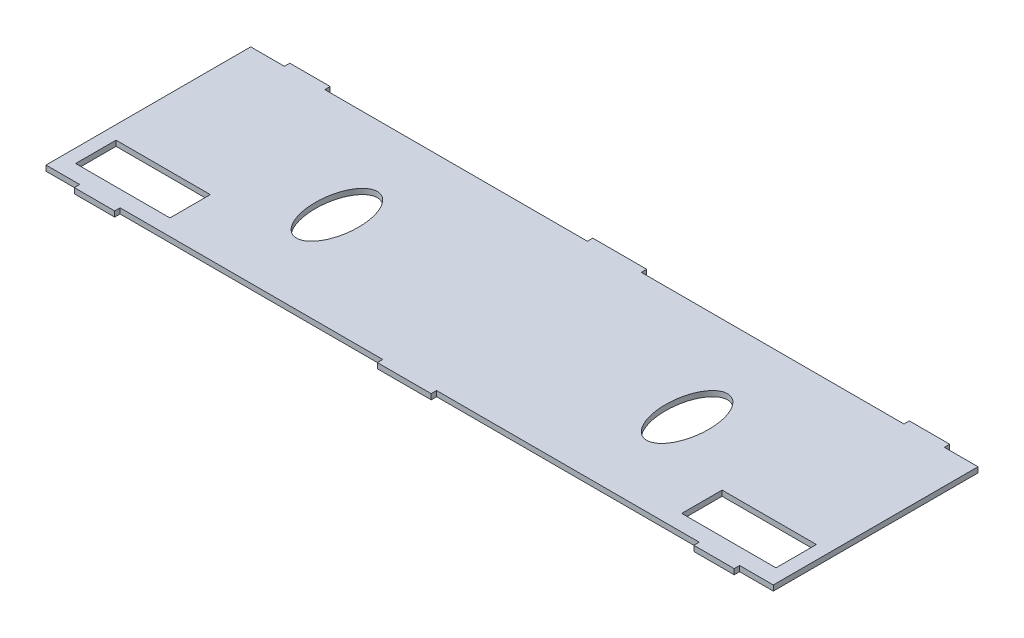
SolidWorks part; units mm, degrees
material "Hexcel AS4C (3000 丝)"
ref_plane "前视基准面" through (0, 0, 0) normal (0, 0, 1) x (1, 0, 0)
ref_plane "上视基准面" through (0, 0, 0) normal (0, 1, 0) x (1, 0, 0)
ref_plane "右视基准面" through (0, 0, 0) normal (1, 0, 0) x (0, 0, -1)
sketch "草图1" plane through (0, 0, 0) normal (0, 1, 0) x (1, 0, 0)
  line L0 (-107.5, 38) -> (-10, 38)
  line L1 (-135, -38) -> (-122.5, -38)
  line L2 (-135, -38) -> (-135, 38)
  line L3 (-135, 38) -> (-122.5, 38)
  line L4 (135, -38) -> (135, 38)
  line L5 (-135, -38) -> (135, 38) construction
  line L6 (-135, 38) -> (135, -38) construction
  line L7 (-122.5, 40) -> (-107.5, 40)
  line L8 (-122.5, 40) -> (-122.5, 38)
  line L9 (10, 38) -> (107.5, 38)
  line L10 (-107.5, 40) -> (-107.5, 38)
  line L11 (-122.5, 40) -> (-107.5, 38) construction
  line L12 (-122.5, 38) -> (-107.5, 40) construction
  line L13 (122.5, 38) -> (135, 38)
  line L14 (-10, 38) -> (-10, 40)
  line L15 (-10, 40) -> (10, 40)
  line L16 (10, 38) -> (10, 40)
  line L17 (-10, 38) -> (10, 40) construction
  line L18 (-10, 40) -> (10, 38) construction
  line L19 (107.5, 40) -> (122.5, 40)
  line L20 (107.5, 40) -> (107.5, 38)
  line L21 (-135, 0) -> (135, 0) construction
  line L22 (122.5, 40) -> (122.5, 38)
  line L23 (107.5, 40) -> (122.5, 38) construction
  line L24 (107.5, 38) -> (122.5, 40) construction
  line L25 (107.5, -40) -> (107.5, -38)
  line L26 (107.5, -40) -> (122.5, -40)
  line L27 (122.5, -40) -> (122.5, -38)
  line L28 (-10, -38) -> (-10, -40)
  line L29 (10, -38) -> (10, -40)
  line L30 (-10, -40) -> (10, -40)
  line L31 (-107.5, -40) -> (-107.5, -38)
  line L32 (-122.5, -40) -> (-122.5, -38)
  line L33 (-122.5, -40) -> (-107.5, -40)
  line L34 (-107.5, -38) -> (-10, -38)
  line L35 (10, -38) -> (107.5, -38)
  line L36 (122.5, -38) -> (135, -38)
  line L37 (0, -39) -> (0, 39) construction
  ellipse E0 centre (-65, 0) end of major axis (-65, 15) minor radius 8
  ellipse E1 centre (65, 0) end of major axis (65, 15) minor radius 8
  point P0 (0, 0)
  point P6 (-115, 39)
  point P11 (0, 39)
  point P16 (115, 39)
  point P24 (0, 0)
  point P36 (-115, -39)
  point P46 (0, 0)
  dimension "D1" = 270
  dimension "D2" = 76
  dimension "D3" = 15
  dimension "D4" = 2
  dimension "D5" = 20
  dimension "D6" = 2
  dimension "D7" = 20
  dimension "D8" = 65
  dimension "D9" = 2
  dimension "D10" = 15
  dimension "D11" = 20
  dimension "D12" = 15
  dimension "D13" = 8
extrude "凸台-拉伸1" add sketch "草图1" along normal blind 2
sketch "草图2" plane through (0, 0, 0) normal (0, -1, 0) x (1, 0, 0)
  line L0 (-135, -38) -> (-135, 38) construction
  line L1 (-95, 17) -> (-130, 17)
  line L2 (-95, 17) -> (-95, 32)
  line L3 (-95, 32) -> (-130, 32)
  line L4 (-130, 17) -> (-130, 32)
  line L5 (-95, 17) -> (-130, 32) construction
  line L6 (-95, 32) -> (-130, 17) construction
  line L7 (-107.5, 38) -> (-10, 38) construction
  point P0 (-112.5, 24.5)
  dimension "D1" = 5
  dimension "D2" = 6
  dimension "D3" = 15
  dimension "D4" = 35
extrude "切除-拉伸1" cut sketch "草图2" against normal through all
mirror "镜向1" about plane through (0, 0, 0) normal (1, 0, 0) of "切除-拉伸1"
